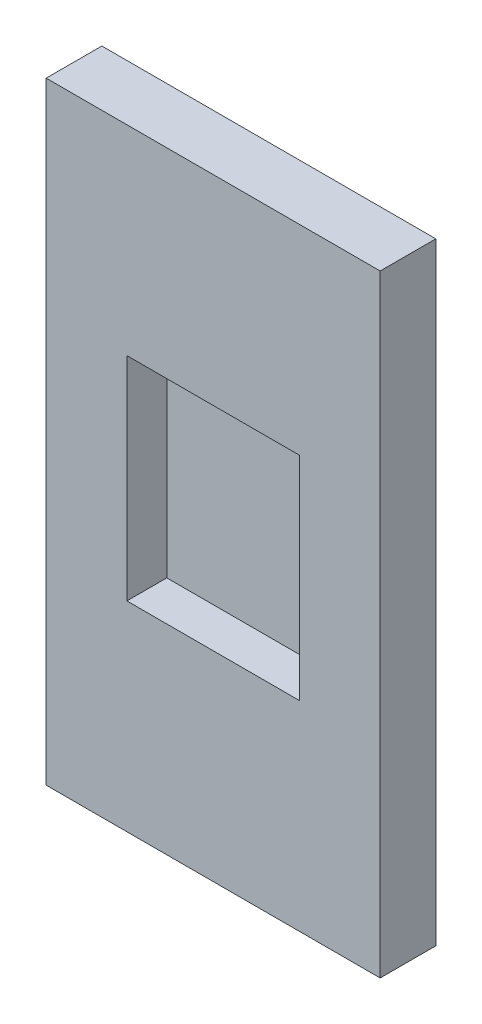
SolidWorks part; units mm, degrees
ref_plane "정면" through (0, 0, 0) normal (0, 0, 1) x (1, 0, 0)
ref_plane "윗면" through (0, 0, 0) normal (0, 1, 0) x (1, 0, 0)
ref_plane "우측면" through (0, 0, 0) normal (1, 0, 0) x (0, 0, -1)
sketch "스케치1" plane through (0, 0, 0) normal (0, 0, 1) x (1, 0, 0)
  line L1 (-9, -16.5) -> (9, -16.5)
  line L2 (-9, -16.5) -> (-9, 16.5)
  line L3 (-9, 16.5) -> (9, 16.5)
  line L4 (9, -16.5) -> (9, 16.5)
  line L5 (-9, -16.5) -> (9, 16.5) construction
  line L6 (-9, 16.5) -> (9, -16.5) construction
  point P0 (0, 0)
  dimension "D1" = 18
  dimension "D2" = 33
extrude "보스-돌출1" add sketch "스케치1" along normal blind 3
sketch "스케치2" plane through (0, 0, 3) normal (0, 0, 1) x (1, 0, 0)
  line L1 (-4.65, -5.725) -> (4.65, -5.725)
  line L2 (-4.65, -5.725) -> (-4.65, 5.725)
  line L3 (-4.65, 5.725) -> (4.65, 5.725)
  line L4 (4.65, -5.725) -> (4.65, 5.725)
  line L5 (-4.65, -5.725) -> (4.65, 5.725) construction
  line L6 (-4.65, 5.725) -> (4.65, -5.725) construction
  point P1 (0, 0)
  dimension "D1" = 9.3
  dimension "D2" = 11.45
extrude "컷-돌출1" cut sketch "스케치2" against normal blind 2.15
